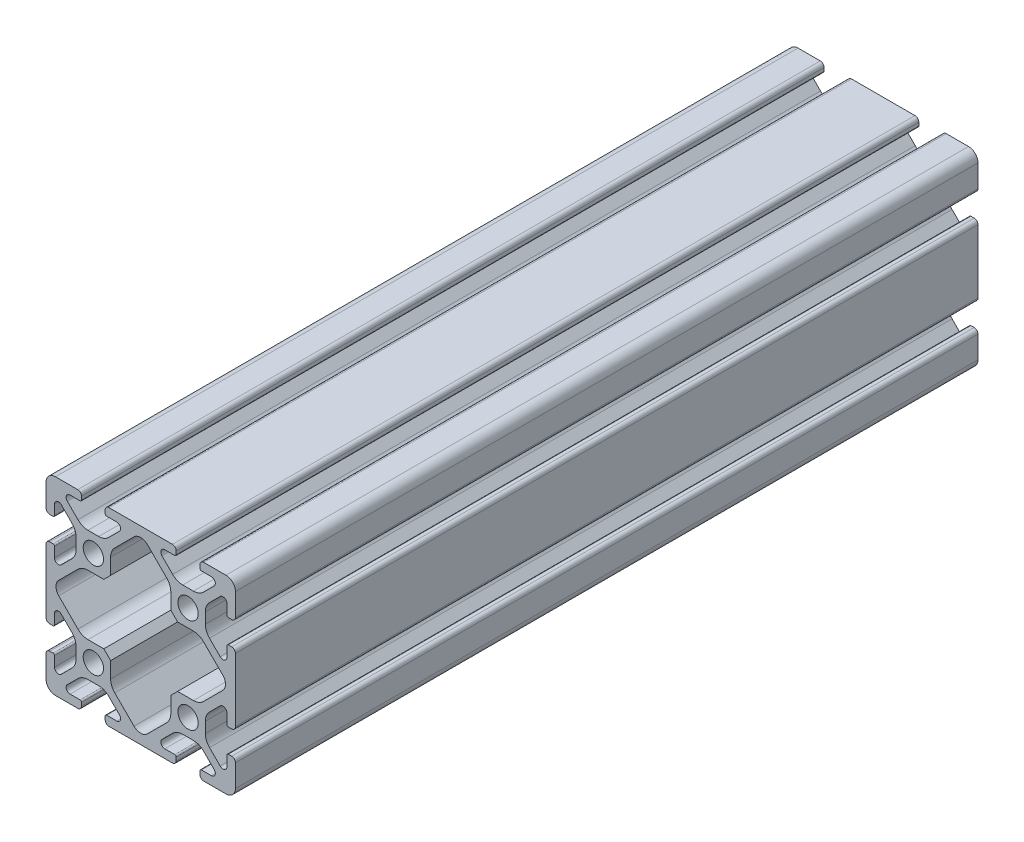
SolidWorks part; units mm, degrees
material "Alliage 1060"
ref_plane "Plan de face" through (0, 0, 0) normal (0, 0, 1) x (1, 0, 0)
ref_plane "Plan de dessus" through (0, 0, 0) normal (0, 1, 0) x (1, 0, 0)
ref_plane "Plan de droite" through (0, 0, 0) normal (1, 0, 0) x (0, 0, -1)
ref_plane "Plan1" through (0, 0, 0) normal (0, 0, -1) x (-1, 0, 0)
sketch "Esquisse1" plane through (0, 0, 0) normal (0, 0, -1) x (-1, 0, 0)
  line L0 (0, 13.3) -> (0, 26.7)
  line L1 (-0.8, 27.5) -> (-1.5, 27.5)
  line L2 (-1.8, 27.2) -> (-1.8, 25.0816)
  line L3 (-3.2196, 24.4936) -> (-5.4713, 26.7453)
  line L4 (-6.35, 28.8666) -> (-6.35, 31.1334)
  line L5 (-5.4713, 33.2547) -> (-3.2196, 35.5064)
  line L6 (-1.8, 34.9184) -> (-1.8, 32.8)
  line L7 (-1.5, 32.5) -> (-0.8, 32.5)
  line L8 (0, 33.3) -> (0, 38)
  line L9 (-2, 40) -> (-6.7, 40)
  line L10 (-7.5, 39.2) -> (-7.5, 38.5)
  line L11 (-7.2, 38.2) -> (-5.0816, 38.2)
  line L12 (-4.4936, 36.7804) -> (-6.7453, 34.5287)
  line L13 (-8.8666, 33.65) -> (-11.1334, 33.65)
  line L14 (-13.2547, 34.5287) -> (-15.5064, 36.7804)
  line L15 (-14.9184, 38.2) -> (-12.8, 38.2)
  line L16 (-12.5, 38.5) -> (-12.5, 39.2)
  line L17 (-13.3, 40) -> (-26.7, 40)
  line L18 (-27.5, 39.2) -> (-27.5, 38.5)
  line L19 (-27.2, 38.2) -> (-25.0816, 38.2)
  line L20 (-24.4936, 36.7804) -> (-26.7453, 34.5287)
  line L21 (-28.8666, 33.65) -> (-31.1334, 33.65)
  line L22 (-33.2547, 34.5287) -> (-35.5064, 36.7804)
  line L23 (-34.9184, 38.2) -> (-32.8, 38.2)
  line L24 (-32.5, 38.5) -> (-32.5, 39.2)
  line L25 (-33.3, 40) -> (-38, 40)
  line L26 (-40, 38) -> (-40, 33.3)
  line L27 (-39.2, 32.5) -> (-38.5, 32.5)
  line L28 (-38.2, 32.8) -> (-38.2, 34.9184)
  line L29 (-36.7804, 35.5064) -> (-34.5287, 33.2547)
  line L30 (-33.65, 31.1334) -> (-33.65, 28.8666)
  line L31 (-34.5287, 26.7453) -> (-36.7804, 24.4936)
  line L32 (-38.2, 25.0816) -> (-38.2, 27.2)
  line L33 (-38.5, 27.5) -> (-39.2, 27.5)
  line L34 (-40, 26.7) -> (-40, 13.3)
  line L35 (-39.2, 12.5) -> (-38.5, 12.5)
  line L36 (-38.2, 12.8) -> (-38.2, 14.9184)
  line L37 (-36.7804, 15.5064) -> (-34.5287, 13.2547)
  line L38 (-33.65, 11.1334) -> (-33.65, 8.8666)
  line L39 (-34.5287, 6.7453) -> (-36.7804, 4.4936)
  line L40 (-38.2, 5.0816) -> (-38.2, 7.2)
  line L41 (-38.5, 7.5) -> (-39.2, 7.5)
  line L42 (-40, 6.7) -> (-40, 2)
  line L43 (-38, 0) -> (-33.3, 0)
  line L44 (-32.5, 0.8) -> (-32.5, 1.5)
  line L45 (-32.8, 1.8) -> (-34.9184, 1.8)
  line L46 (-35.5064, 3.2196) -> (-33.2547, 5.4713)
  line L47 (-31.1334, 6.35) -> (-28.8666, 6.35)
  line L48 (-26.7453, 5.4713) -> (-24.4936, 3.2196)
  line L49 (-25.0816, 1.8) -> (-27.2, 1.8)
  line L50 (-27.5, 1.5) -> (-27.5, 0.8)
  line L51 (-26.7, 0) -> (-13.3, 0)
  line L52 (-12.5, 0.8) -> (-12.5, 1.5)
  line L53 (-12.8, 1.8) -> (-14.9184, 1.8)
  line L54 (-15.5064, 3.2196) -> (-13.2547, 5.4713)
  line L55 (-11.1334, 6.35) -> (-8.8666, 6.35)
  line L56 (-6.7453, 5.4713) -> (-4.4936, 3.2196)
  line L57 (-5.0816, 1.8) -> (-7.2, 1.8)
  line L58 (-7.5, 1.5) -> (-7.5, 0.8)
  line L59 (-6.7, 0) -> (-2, 0)
  line L60 (0, 2) -> (0, 6.7)
  line L61 (-0.8, 7.5) -> (-1.5, 7.5)
  line L62 (-1.8, 7.2) -> (-1.8, 5.0816)
  line L63 (-3.2196, 4.4936) -> (-5.4713, 6.7453)
  line L64 (-6.35, 8.8666) -> (-6.35, 11.1334)
  line L65 (-5.4713, 13.2547) -> (-3.2196, 15.5064)
  line L66 (-1.8, 14.9184) -> (-1.8, 12.8)
  line L67 (-1.5, 12.5) -> (-0.8, 12.5)
  line L68 (-12.2079, 13.65) -> (-13.65, 12.2079)
  line L69 (-13.65, 12.2079) -> (-13.65, 8.8654)
  line L70 (-14.5287, 6.7441) -> (-18.5858, 2.687)
  line L71 (-21.4142, 2.687) -> (-25.4713, 6.7441)
  line L72 (-26.35, 8.8654) -> (-26.35, 12.2079)
  line L73 (-26.35, 12.2079) -> (-27.0711, 12.9289)
  line L74 (-27.0711, 12.9289) -> (-27.7921, 13.65)
  line L75 (-27.7921, 13.65) -> (-31.1346, 13.65)
  line L76 (-33.2559, 14.5287) -> (-37.313, 18.5858)
  line L77 (-37.313, 21.4142) -> (-33.2559, 25.4713)
  line L78 (-31.1346, 26.35) -> (-27.7921, 26.35)
  line L79 (-27.7921, 26.35) -> (-27.0711, 27.0711)
  line L80 (-27.0711, 27.0711) -> (-26.35, 27.7921)
  line L81 (-26.35, 27.7921) -> (-26.35, 31.1346)
  line L82 (-25.4713, 33.2559) -> (-21.4142, 37.313)
  line L83 (-18.5858, 37.313) -> (-14.5287, 33.2559)
  line L84 (-13.65, 31.1346) -> (-13.65, 27.7921)
  line L85 (-13.65, 27.7921) -> (-12.2079, 26.35)
  line L86 (-12.2079, 26.35) -> (-8.8654, 26.35)
  line L87 (-6.7441, 25.4713) -> (-2.687, 21.4142)
  line L88 (-2.687, 18.5858) -> (-6.7441, 14.5287)
  line L89 (-8.8654, 13.65) -> (-12.2079, 13.65)
  arc A0 (-0.8, 12.5) -> (0, 13.3) centre (-0.8, 13.3) ccw
  arc A1 (0, 26.7) -> (-0.8, 27.5) centre (-0.8, 26.7) ccw
  arc A2 (-1.5, 27.5) -> (-1.8, 27.2) centre (-1.5, 27.2) ccw
  arc A3 (-1.8, 25.0816) -> (-3.2196, 24.4936) centre (-2.6316, 25.0816) cw
  arc A4 (-5.4713, 26.7453) -> (-6.35, 28.8666) centre (-3.35, 28.8666) cw
  arc A5 (-6.35, 31.1334) -> (-5.4713, 33.2547) centre (-3.35, 31.1334) cw
  arc A6 (-3.2196, 35.5064) -> (-1.8, 34.9184) centre (-2.6316, 34.9184) cw
  arc A7 (-1.8, 32.8) -> (-1.5, 32.5) centre (-1.5, 32.8) ccw
  arc A8 (-0.8, 32.5) -> (0, 33.3) centre (-0.8, 33.3) ccw
  arc A9 (0, 38) -> (-2, 40) centre (-2, 38) ccw
  arc A10 (-6.7, 40) -> (-7.5, 39.2) centre (-6.7, 39.2) ccw
  arc A11 (-7.5, 38.5) -> (-7.2, 38.2) centre (-7.2, 38.5) ccw
  arc A12 (-5.0816, 38.2) -> (-4.4936, 36.7804) centre (-5.0816, 37.3684) cw
  arc A13 (-6.7453, 34.5287) -> (-8.8666, 33.65) centre (-8.8666, 36.65) cw
  arc A14 (-11.1334, 33.65) -> (-13.2547, 34.5287) centre (-11.1334, 36.65) cw
  arc A15 (-15.5064, 36.7804) -> (-14.9184, 38.2) centre (-14.9184, 37.3684) cw
  arc A16 (-12.8, 38.2) -> (-12.5, 38.5) centre (-12.8, 38.5) ccw
  arc A17 (-12.5, 39.2) -> (-13.3, 40) centre (-13.3, 39.2) ccw
  arc A18 (-26.7, 40) -> (-27.5, 39.2) centre (-26.7, 39.2) ccw
  arc A19 (-27.5, 38.5) -> (-27.2, 38.2) centre (-27.2, 38.5) ccw
  arc A20 (-25.0816, 38.2) -> (-24.4936, 36.7804) centre (-25.0816, 37.3684) cw
  arc A21 (-26.7453, 34.5287) -> (-28.8666, 33.65) centre (-28.8666, 36.65) cw
  arc A22 (-31.1334, 33.65) -> (-33.2547, 34.5287) centre (-31.1334, 36.65) cw
  arc A23 (-35.5064, 36.7804) -> (-34.9184, 38.2) centre (-34.9184, 37.3684) cw
  arc A24 (-32.8, 38.2) -> (-32.5, 38.5) centre (-32.8, 38.5) ccw
  arc A25 (-32.5, 39.2) -> (-33.3, 40) centre (-33.3, 39.2) ccw
  arc A26 (-38, 40) -> (-40, 38) centre (-38, 38) ccw
  arc A27 (-40, 33.3) -> (-39.2, 32.5) centre (-39.2, 33.3) ccw
  arc A28 (-38.5, 32.5) -> (-38.2, 32.8) centre (-38.5, 32.8) ccw
  arc A29 (-38.2, 34.9184) -> (-36.7804, 35.5064) centre (-37.3684, 34.9184) cw
  arc A30 (-34.5287, 33.2547) -> (-33.65, 31.1334) centre (-36.65, 31.1334) cw
  arc A31 (-33.65, 28.8666) -> (-34.5287, 26.7453) centre (-36.65, 28.8666) cw
  arc A32 (-36.7804, 24.4936) -> (-38.2, 25.0816) centre (-37.3684, 25.0816) cw
  arc A33 (-38.2, 27.2) -> (-38.5, 27.5) centre (-38.5, 27.2) ccw
  arc A34 (-39.2, 27.5) -> (-40, 26.7) centre (-39.2, 26.7) ccw
  arc A35 (-40, 13.3) -> (-39.2, 12.5) centre (-39.2, 13.3) ccw
  arc A36 (-38.5, 12.5) -> (-38.2, 12.8) centre (-38.5, 12.8) ccw
  arc A37 (-38.2, 14.9184) -> (-36.7804, 15.5064) centre (-37.3684, 14.9184) cw
  arc A38 (-34.5287, 13.2547) -> (-33.65, 11.1334) centre (-36.65, 11.1334) cw
  arc A39 (-33.65, 8.8666) -> (-34.5287, 6.7453) centre (-36.65, 8.8666) cw
  arc A40 (-36.7804, 4.4936) -> (-38.2, 5.0816) centre (-37.3684, 5.0816) cw
  arc A41 (-38.2, 7.2) -> (-38.5, 7.5) centre (-38.5, 7.2) ccw
  arc A42 (-39.2, 7.5) -> (-40, 6.7) centre (-39.2, 6.7) ccw
  arc A43 (-40, 2) -> (-38, 0) centre (-38, 2) ccw
  arc A44 (-33.3, 0) -> (-32.5, 0.8) centre (-33.3, 0.8) ccw
  arc A45 (-32.5, 1.5) -> (-32.8, 1.8) centre (-32.8, 1.5) ccw
  arc A46 (-34.9184, 1.8) -> (-35.5064, 3.2196) centre (-34.9184, 2.6316) cw
  arc A47 (-33.2547, 5.4713) -> (-31.1334, 6.35) centre (-31.1334, 3.35) cw
  arc A48 (-28.8666, 6.35) -> (-26.7453, 5.4713) centre (-28.8666, 3.35) cw
  arc A49 (-24.4936, 3.2196) -> (-25.0816, 1.8) centre (-25.0816, 2.6316) cw
  arc A50 (-27.2, 1.8) -> (-27.5, 1.5) centre (-27.2, 1.5) ccw
  arc A51 (-27.5, 0.8) -> (-26.7, 0) centre (-26.7, 0.8) ccw
  arc A52 (-13.3, 0) -> (-12.5, 0.8) centre (-13.3, 0.8) ccw
  arc A53 (-12.5, 1.5) -> (-12.8, 1.8) centre (-12.8, 1.5) ccw
  arc A54 (-14.9184, 1.8) -> (-15.5064, 3.2196) centre (-14.9184, 2.6316) cw
  arc A55 (-13.2547, 5.4713) -> (-11.1334, 6.35) centre (-11.1334, 3.35) cw
  arc A56 (-8.8666, 6.35) -> (-6.7453, 5.4713) centre (-8.8666, 3.35) cw
  arc A57 (-4.4936, 3.2196) -> (-5.0816, 1.8) centre (-5.0816, 2.6316) cw
  arc A58 (-7.2, 1.8) -> (-7.5, 1.5) centre (-7.2, 1.5) ccw
  arc A59 (-7.5, 0.8) -> (-6.7, 0) centre (-6.7, 0.8) ccw
  arc A60 (-2, 0) -> (0, 2) centre (-2, 2) ccw
  arc A61 (0, 6.7) -> (-0.8, 7.5) centre (-0.8, 6.7) ccw
  arc A62 (-1.5, 7.5) -> (-1.8, 7.2) centre (-1.5, 7.2) ccw
  arc A63 (-1.8, 5.0816) -> (-3.2196, 4.4936) centre (-2.6316, 5.0816) cw
  arc A64 (-5.4713, 6.7453) -> (-6.35, 8.8666) centre (-3.35, 8.8666) cw
  arc A65 (-6.35, 11.1334) -> (-5.4713, 13.2547) centre (-3.35, 11.1334) cw
  arc A66 (-3.2196, 15.5064) -> (-1.8, 14.9184) centre (-2.6316, 14.9184) cw
  arc A67 (-1.8, 12.8) -> (-1.5, 12.5) centre (-1.5, 12.8) ccw
  circle A68 centre (-10, 10) radius 2.15
  circle A69 centre (-10, 30) radius 2.15
  circle A70 centre (-30, 10) radius 2.15
  circle A71 centre (-30, 30) radius 2.15
  arc A72 (-13.65, 8.8654) -> (-14.5287, 6.7441) centre (-16.65, 8.8654) cw
  arc A73 (-18.5858, 2.687) -> (-21.4142, 2.687) centre (-20, 4.1012) cw
  arc A74 (-25.4713, 6.7441) -> (-26.35, 8.8654) centre (-23.35, 8.8654) cw
  arc A75 (-31.1346, 13.65) -> (-33.2559, 14.5287) centre (-31.1346, 16.65) cw
  arc A76 (-37.313, 18.5858) -> (-37.313, 21.4142) centre (-35.8988, 20) cw
  arc A77 (-33.2559, 25.4713) -> (-31.1346, 26.35) centre (-31.1346, 23.35) cw
  arc A78 (-26.35, 31.1346) -> (-25.4713, 33.2559) centre (-23.35, 31.1346) cw
  arc A79 (-21.4142, 37.313) -> (-18.5858, 37.313) centre (-20, 35.8988) cw
  arc A80 (-14.5287, 33.2559) -> (-13.65, 31.1346) centre (-16.65, 31.1346) cw
  arc A81 (-8.8654, 26.35) -> (-6.7441, 25.4713) centre (-8.8654, 23.35) cw
  arc A82 (-2.687, 21.4142) -> (-2.687, 18.5858) centre (-4.1012, 20) cw
  arc A83 (-6.7441, 14.5287) -> (-8.8654, 13.65) centre (-8.8654, 16.65) cw
extrude "Extrusion1" add sketch "Esquisse1" against normal blind 156.8
